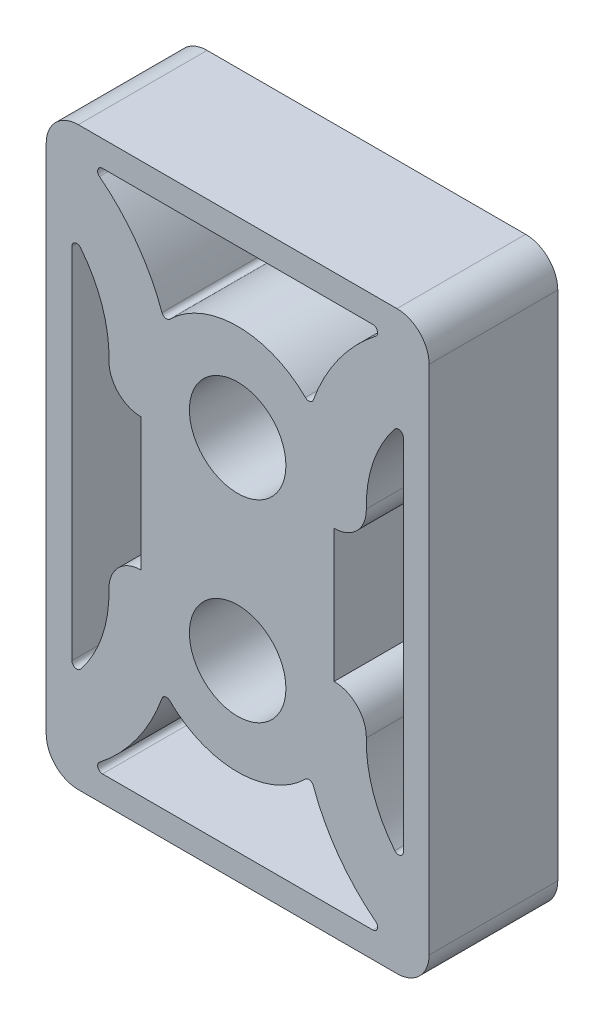
SolidWorks part; units mm, degrees
ref_plane "Front Plane" through (0, 0, 0) normal (0, 0, 1) x (1, 0, 0)
ref_plane "Top Plane" through (0, 0, 0) normal (0, 1, 0) x (1, 0, 0)
ref_plane "Right Plane" through (0, 0, 0) normal (1, 0, 0) x (0, 0, -1)
sketch "Sketch1" plane through (0, 0, 0) normal (0, 0, 1) x (1, 0, 0)
  line L0 (0, 3) -> (0, -3) construction
  line L1 (0, 3) -> (0, -3) construction
  line L2 (3, 3) -> (3, -3)
  line L3 (-3, 3) -> (-3, -3)
  circle A0 centre (0, 3) radius 1.5
  circle A1 centre (0, -3) radius 1.5
  arc A2 (3, 3) -> (-3, 3) centre (0, 3) ccw
  arc A3 (-3, -3) -> (3, -3) centre (0, -3) ccw
  point P2 (0, 0)
  point P7 (0, 0)
  dimension "D2" = 3
  dimension "D1" = 6
  dimension "D3" = 6
extrude "Boss-Extrude1" add sketch "Sketch1" along normal blind 4
sketch "Sketch3" plane through (0, 0, 0) normal (0, 0, 1) x (1, 0, 0)
  line L0 (-3, 3) -> (-3, -3) construction
  line L1 (3, -3) -> (3, 3) construction
  line L2 (-3, 3) -> (-3, -3) construction
  line L3 (3, -3) -> (3, 3) construction
  line L4 (0, 3) -> (0, -3) construction
  line L5 (-5.15, 8.15) -> (5.15, 8.15) construction
  line L6 (-5.15, 8.15) -> (-5.15, -8.15) construction
  line L7 (-5.15, -8.15) -> (5.15, -8.15) construction
  line L8 (5.15, 8.15) -> (5.15, -8.15) construction
  line L9 (-5.15, 8.15) -> (5.15, -8.15) construction
  line L10 (-5.15, -8.15) -> (5.15, 8.15) construction
  line L11 (-3, 0) -> (3, 0) construction
  line L12 (-5.95, 8.95) -> (-5.95, -8.95)
  line L13 (-5.95, -8.95) -> (5.95, -8.95)
  line L14 (5.95, 8.95) -> (5.95, -8.95)
  line L15 (-5.95, 8.95) -> (5.95, 8.95)
  line L16 (3, 2.0608) -> (3, 3)
  line L21 (3, -2.0608) -> (3, -3)
  line L24 (-3, -2.0608) -> (-3, -3)
  line L27 (-3, 2.0608) -> (-3, 3)
  line L28 (5.15, 5.9705) -> (5.15, -5.9705)
  line L29 (4.6635, -8.15) -> (-4.6635, -8.15)
  line L30 (-5.15, -5.9705) -> (-5.15, 5.9705)
  line L31 (-4.6635, 8.15) -> (4.6635, 8.15)
  arc A0 (-3, -3) -> (3, -3) centre (0, -3) ccw construction
  arc A1 (3, 3) -> (-3, 3) centre (0, 3) ccw construction
  arc A3 (-3, -3) -> (3, -3) centre (0, -3) ccw construction
  arc A5 (3, 3) -> (-3, 3) centre (0, 3) ccw construction
  arc A6 (2.9994, 3.0608) -> (7.65, 8.15) centre (7.9984, 3.1621) cw construction
  arc A7 (7.5803, 9.1476) -> (1.9996, 3.0405) centre (7.9984, 3.1621) ccw construction
  arc A8 (7.7197, 7.1524) -> (3.9992, 3.0811) centre (7.9984, 3.1621) ccw construction
  arc A9 (7.7197, 7.1524) -> (7.5803, 9.1476) centre (7.65, 8.15) ccw construction
  arc A10 (1.9996, 3.0405) -> (3.9992, 3.0811) centre (2.9994, 3.0608) ccw construction
  arc A11 (2.2733, 4.9576) -> (4.6635, 8.15) centre (7.9984, 3.1621) cw
  arc A16 (3.9992, 3.0811) -> (5.15, 5.9705) centre (7.9984, 3.1621) cw
  arc A17 (3.9992, 3.0811) -> (3, 2.0608) centre (2.9994, 3.0608) cw
  arc A18 (2.2733, 4.9576) -> (3, 3) centre (0, 3) cw
  arc A19 (2.2733, -4.9576) -> (3, -3) centre (0, -3) ccw
  arc A20 (2.2733, -4.9576) -> (4.6635, -8.15) centre (7.9984, -3.1621) ccw
  arc A21 (3.9992, -3.0811) -> (5.15, -5.9705) centre (7.9984, -3.1621) ccw
  arc A22 (3.9992, -3.0811) -> (3, -2.0608) centre (2.9994, -3.0608) ccw
  arc A23 (-2.2733, -4.9576) -> (-3, -3) centre (0, -3) cw
  arc A24 (-2.2733, -4.9576) -> (-4.6635, -8.15) centre (-7.9984, -3.1621) cw
  arc A25 (-3.9992, -3.0811) -> (-5.15, -5.9705) centre (-7.9984, -3.1621) cw
  arc A26 (-3.9992, -3.0811) -> (-3, -2.0608) centre (-2.9994, -3.0608) cw
  arc A27 (-2.2733, 4.9576) -> (-3, 3) centre (0, 3) ccw
  arc A28 (-2.2733, 4.9576) -> (-4.6635, 8.15) centre (-7.9984, 3.1621) ccw
  arc A29 (-3.9992, 3.0811) -> (-5.15, 5.9705) centre (-7.9984, 3.1621) ccw
  arc A30 (-3.9992, 3.0811) -> (-3, 2.0608) centre (-2.9994, 3.0608) ccw
  point P3 (0, 0)
  point P15 (4.3074, 6.5351)
  dimension "D3" = 2
  dimension "D4" = 4
  dimension "D5" = 2.5
  dimension "D6" = 0.8
  dimension "D1" = 17.9
  dimension "D2" = 11.9
extrude "Boss-Extrude2" add sketch "Sketch3" along normal blind 4
fillet "Fillet1" radius 1 4 edges at (-5.95, 8.95, 2) (-5.95, -8.95, 2) (5.95, -8.95, 2) (5.95, 8.95, 2)
fillet "Fillet2" radius 0.15 12 edges at (-5.15, -5.9705, 2) (5.15, -5.9705, 2) (4.6635, -8.15, 2) (-4.6635, -8.15, 2) (2.2733, -4.9576, 2) (-2.2733, -4.9576, 2) (-5.15, 5.9705, 2) (5.15, 5.9705, 2) (4.6635, 8.15, 2) (2.2733, 4.9576, 2) (-2.2733, 4.9576, 2) (-4.6635, 8.15, 2)
